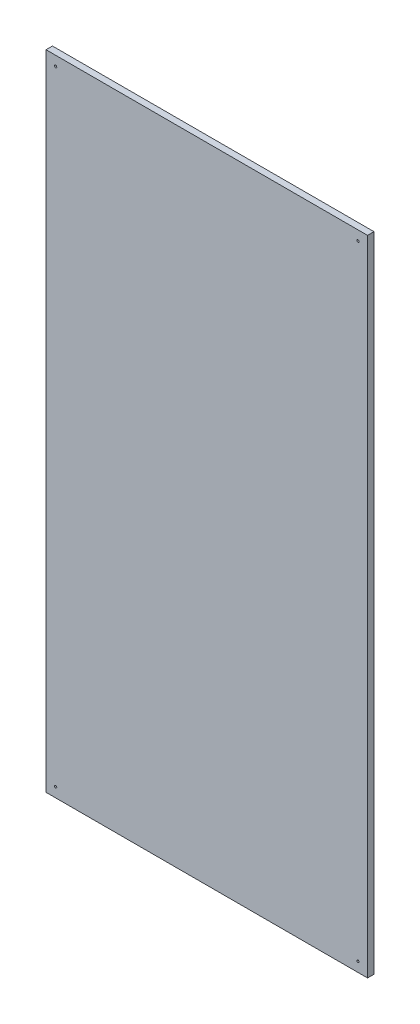
SolidWorks part; units mm, degrees
ref_plane "Plan de face" through (0, 0, 0) normal (0, 0, 1) x (1, 0, 0)
ref_plane "Plan de dessus" through (0, 0, 0) normal (0, 1, 0) x (1, 0, 0)
ref_plane "Plan de droite" through (0, 0, 0) normal (1, 0, 0) x (0, 0, -1)
sketch "Esquisse1" plane through (0, 0, 0) normal (0, 0, 1) x (1, 0, 0)
  line L0 (0, 0) -> (0, -50000) construction
  line L1 (-250, 500) -> (250, 500)
  line L2 (-250, 500) -> (-250, -500)
  line L3 (-250, -500) -> (250, -500)
  line L4 (250, 500) -> (250, -500)
  line L5 (-250, 500) -> (250, -500) construction
  line L6 (-250, -500) -> (250, 500) construction
  line L7 (0, 0) -> (50000, 0) construction
  line L8 (235, 485) -> (235, 500) construction
  line L9 (235, 485) -> (250, 485) construction
  circle A0 centre (235, 485) radius 1.75
  circle A2 centre (235, -485) radius 1.75
  circle A8 centre (-235, -485) radius 1.75
  circle A9 centre (-235, 485) radius 1.75
  point P0 (0, 0)
  dimension "D3" = 3.5
  dimension "D1" = 1000
  dimension "D2" = 500
  dimension "D4" = 15
extrude "Boss.-Extru.1" add sketch "Esquisse1" along normal blind 10
